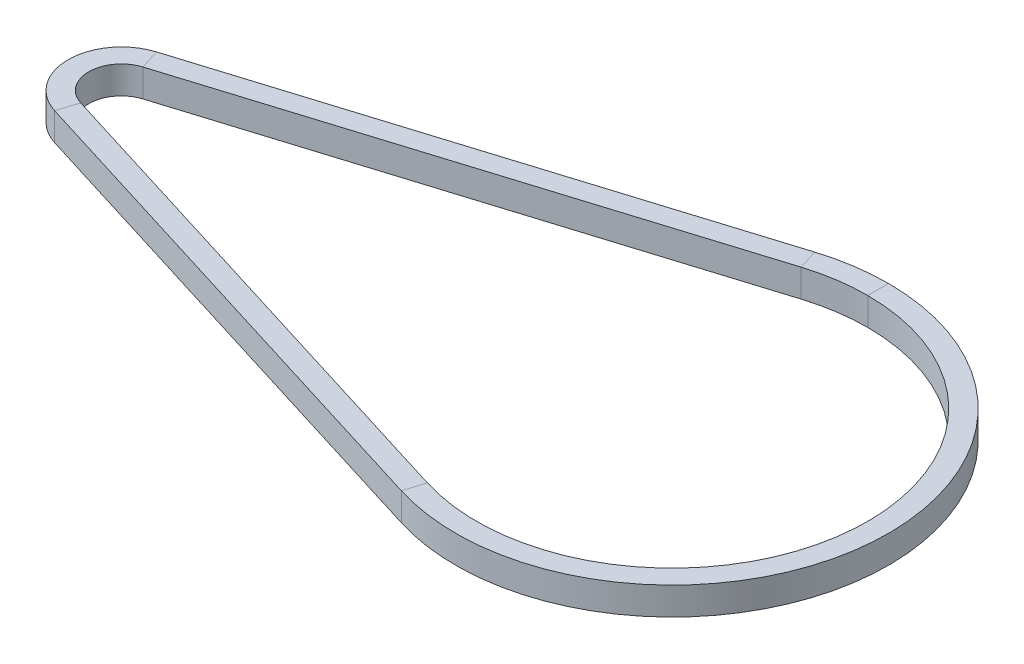
SolidWorks part; units mm, degrees
ref_plane "Front Plane" through (0, 0, 0) normal (0, 0, 1) x (1, 0, 0)
ref_plane "Top Plane" through (0, 0, 0) normal (0, 1, 0) x (1, 0, 0)
ref_plane "Right Plane" through (0, 0, 0) normal (1, 0, 0) x (0, 0, -1)
sketch "Sketch1" plane through (0, 0, 0) normal (0, 1, 0) x (1, 0, 0)
  line L0 (0, 0) -> (115.3838, 0) construction
  line L1 (115.3838, 0) -> (-96.6527, 0) construction
  line L2 (-1.3917, 4.4892) -> (71.1381, 26.9736)
  line L3 (-1.3917, -4.4892) -> (71.1381, -26.9736)
  arc A0 (-1.3917, 4.4892) -> (-1.3917, -4.4892) centre (0, 0) ccw
  arc A1 (71.1381, -26.9736) -> (71.1381, 26.9736) centre (79.5, 0) ccw construction
  arc A2 (71.1381, -26.9736) -> (71.1381, 26.9736) centre (79.5, 0) ccw
  arc A3 (71.1381, -26.9736) -> (69.6428, 26.4638) centre (79.5, 0) ccw construction
  dimension "D1" = 56.48
  dimension "D3" = 9.4
  dimension "D2" = 79.5
ref_plane "Plane1" through (79.5, 0, 0) normal (1, 0, 0) x (0, 0, -1)
sketch "Sketch2" plane through (79.5, 0, 0) normal (1, 0, 0) x (0, 0, -1)
  line L0 (28.24, 0) -> (-28.24, 0) construction
  line L1 (44.8101, 0) -> (-28.24, 0) construction
  line L3 (31.24, -2) -> (28.24, -2)
  line L4 (31.24, -2) -> (31.24, 2)
  line L5 (31.24, 2) -> (28.24, 2)
  line L6 (28.24, -2) -> (28.24, 2)
  dimension "D1" = 28.24
  dimension "D2" = 3
  dimension "D3" = 4
sweep "Sweep1" add profiles "Sketch2" path "Sketch1"
